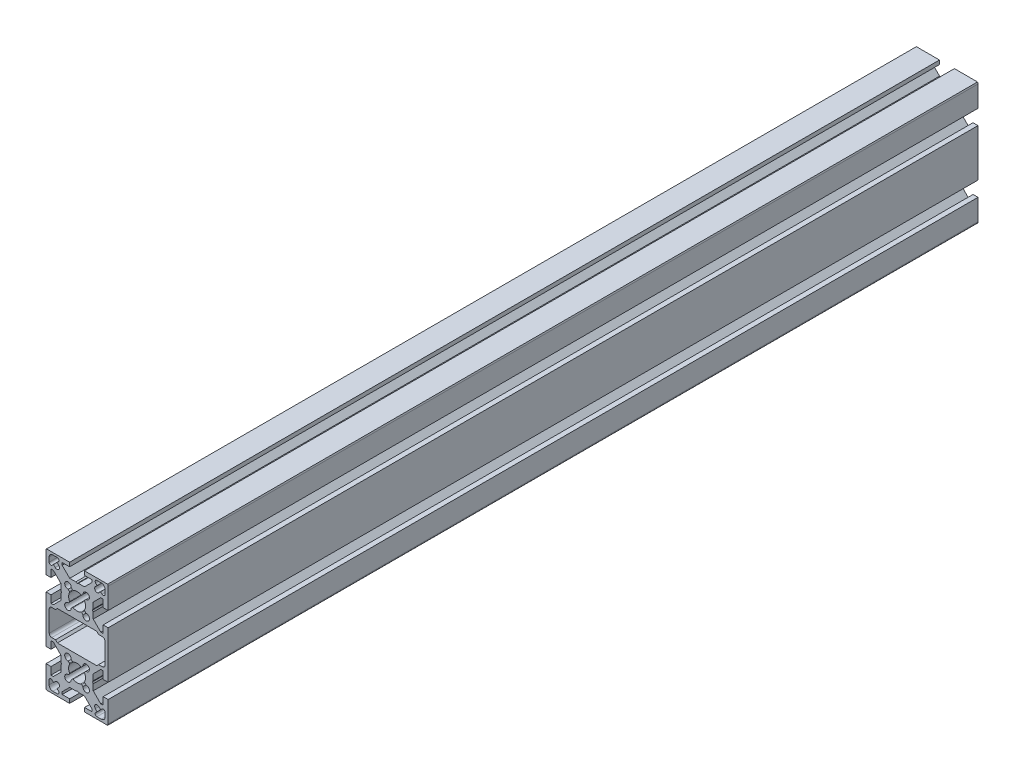
SolidWorks part; units mm, degrees
material "6061 Alloy"
ref_plane "Front Plane" through (0, 0, 0) normal (0, 0, 1) x (1, 0, 0)
ref_plane "Top Plane" through (0, 0, 0) normal (0, 1, 0) x (1, 0, 0)
ref_plane "Right Plane" through (0, 0, 0) normal (1, 0, 0) x (0, 0, -1)
ref_plane "Plane1" through (0, 0, -350) normal (0, 0, -1) x (-1, 0, 0)
sketch "Sketch1" plane through (0, 0, -350) normal (0, 0, -1) x (-1, 0, 0)
  line L0 (12.5, -15.5) -> (10.5, -15.5)
  line L1 (10.5, -15.5) -> (10.5, -18.5)
  line L2 (10.5, -18.5) -> (9.5355, -18.5)
  line L3 (9.5355, -18.5) -> (6.5, -15.4645)
  line L4 (6.5, -15.4645) -> (6.5, -13.0196)
  line L5 (6.5, -13.0196) -> (6.2, -12.5)
  line L6 (6.2, -12.5) -> (6.5, -11.9804)
  line L7 (6.5, -11.9804) -> (6.5, -9.5355)
  line L8 (6.5, -9.5355) -> (9.5355, -6.5)
  line L9 (9.5355, -6.5) -> (10.5, -6.5)
  line L10 (10.5, -6.5) -> (10.5, -9.5)
  line L11 (10.5, -9.5) -> (12.5, -9.5)
  line L12 (12.5, -9.5) -> (12.5, 9.5)
  line L13 (12.5, 9.5) -> (10.5, 9.5)
  line L14 (10.5, 9.5) -> (10.5, 6.5)
  line L15 (10.5, 6.5) -> (9.5355, 6.5)
  line L16 (9.5355, 6.5) -> (6.5, 9.5355)
  line L17 (6.5, 9.5355) -> (6.5, 11.9804)
  line L18 (6.5, 11.9804) -> (6.2, 12.5)
  line L19 (6.2, 12.5) -> (6.5, 13.0196)
  line L20 (6.5, 13.0196) -> (6.5, 15.4645)
  line L21 (6.5, 15.4645) -> (9.5355, 18.5)
  line L22 (9.5355, 18.5) -> (10.5, 18.5)
  line L23 (10.5, 18.5) -> (10.5, 15.5)
  line L24 (10.5, 15.5) -> (12.5, 15.5)
  line L25 (12.5, 15.5) -> (12.5, 24)
  line L26 (12.3, 24.6) -> (3, 24.6)
  line L27 (3, 24.6) -> (3, 23)
  line L28 (3, 23) -> (6, 23)
  line L29 (6, 23) -> (6, 22.0355)
  line L30 (6, 22.0355) -> (2.9645, 19)
  line L31 (2.9645, 19) -> (0.5196, 19)
  line L32 (0.5196, 19) -> (0, 18.7)
  line L33 (0, 18.7) -> (-0.5196, 19)
  line L34 (-0.5196, 19) -> (-2.9645, 19)
  line L35 (-2.9645, 19) -> (-6, 22.0355)
  line L36 (-6, 22.0355) -> (-6, 23)
  line L37 (-6, 23) -> (-3, 23)
  line L38 (-3, 23) -> (-3, 24.6)
  line L39 (-3, 24.6) -> (-12.3, 24.6)
  line L40 (-12.5, 24) -> (-12.5, 15.5)
  line L41 (-12.5, 15.5) -> (-10.5, 15.5)
  line L42 (-10.5, 15.5) -> (-10.5, 18.5)
  line L43 (-10.5, 18.5) -> (-9.5355, 18.5)
  line L44 (-9.5355, 18.5) -> (-6.5, 15.4645)
  line L45 (-6.5, 15.4645) -> (-6.5, 13.0196)
  line L46 (-6.5, 13.0196) -> (-6.2, 12.5)
  line L47 (-6.2, 12.5) -> (-6.5, 11.9804)
  line L48 (-6.5, 11.9804) -> (-6.5, 9.5355)
  line L49 (-6.5, 9.5355) -> (-9.5355, 6.5)
  line L50 (-9.5355, 6.5) -> (-10.5, 6.5)
  line L51 (-10.5, 6.5) -> (-10.5, 9.5)
  line L52 (-10.5, 9.5) -> (-12.5, 9.5)
  line L53 (-12.5, 9.5) -> (-12.5, -9.5)
  line L54 (-12.5, -9.5) -> (-10.5, -9.5)
  line L55 (-10.5, -9.5) -> (-10.5, -6.5)
  line L56 (-10.5, -6.5) -> (-9.5355, -6.5)
  line L57 (-9.5355, -6.5) -> (-6.5, -9.5355)
  line L58 (-6.5, -9.5355) -> (-6.5, -11.9804)
  line L59 (-6.5, -11.9804) -> (-6.2, -12.5)
  line L60 (-6.2, -12.5) -> (-6.5, -13.0196)
  line L61 (-6.5, -13.0196) -> (-6.5, -15.4645)
  line L62 (-6.5, -15.4645) -> (-9.5355, -18.5)
  line L63 (-9.5355, -18.5) -> (-10.5, -18.5)
  line L64 (-10.5, -18.5) -> (-10.5, -15.5)
  line L65 (-10.5, -15.5) -> (-12.5, -15.5)
  line L66 (-12.5, -15.5) -> (-12.5, -24)
  line L67 (-12.3, -24.6) -> (-3, -24.6)
  line L68 (-3, -24.6) -> (-3, -23)
  line L69 (-3, -23) -> (-6, -23)
  line L70 (-6, -23) -> (-6, -22.0355)
  line L71 (-6, -22.0355) -> (-2.9645, -19)
  line L72 (-2.9645, -19) -> (-0.5196, -19)
  line L73 (-0.5196, -19) -> (0, -18.7)
  line L74 (0, -18.7) -> (0.5196, -19)
  line L75 (0.5196, -19) -> (2.9645, -19)
  line L76 (2.9645, -19) -> (6, -22.0355)
  line L77 (6, -22.0355) -> (6, -23)
  line L78 (6, -23) -> (3, -23)
  line L79 (3, -23) -> (3, -24.6)
  line L80 (3, -24.6) -> (12.3, -24.6)
  line L81 (12.5, -24) -> (12.5, -15.5)
  line L82 (11.2, 4.25) -> (11.2, -4.25)
  line L83 (10.2, -5.25) -> (8.6642, -5.25)
  line L84 (8.6642, -5.25) -> (7.9142, -6)
  line L85 (7.9142, -6) -> (-7.9142, -6)
  line L86 (-7.9142, -6) -> (-8.6642, -5.25)
  line L87 (-8.6642, -5.25) -> (-10.2, -5.25)
  line L88 (-11.2, -4.25) -> (-11.2, 4.25)
  line L89 (-10.2, 5.25) -> (-8.6642, 5.25)
  line L90 (-8.6642, 5.25) -> (-7.9142, 6)
  line L91 (-7.9142, 6) -> (7.9142, 6)
  line L92 (7.9142, 6) -> (8.6642, 5.25)
  line L93 (8.6642, 5.25) -> (10.2, 5.25)
  line L94 (3.0878, -14.3857) -> (3.5825, -14.8804)
  line L95 (2.3804, -16.0825) -> (1.8857, -15.5878)
  line L96 (-1.8857, -15.5878) -> (-2.3804, -16.0825)
  line L97 (-3.5825, -14.8804) -> (-3.0878, -14.3857)
  line L98 (-3.0878, -10.6143) -> (-3.5825, -10.1196)
  line L99 (-2.3804, -8.9175) -> (-1.8857, -9.4122)
  line L100 (1.8857, -9.4122) -> (2.3804, -8.9175)
  line L101 (3.5825, -10.1196) -> (3.0878, -10.6143)
  line L102 (3.0878, 10.6143) -> (3.5825, 10.1196)
  line L103 (2.3804, 8.9175) -> (1.8857, 9.4122)
  line L104 (-1.8857, 9.4122) -> (-2.3804, 8.9175)
  line L105 (-3.5825, 10.1196) -> (-3.0878, 10.6143)
  line L106 (-3.0878, 14.3857) -> (-3.5825, 14.8804)
  line L107 (-2.3804, 16.0825) -> (-1.8857, 15.5878)
  line L108 (1.8857, 15.5878) -> (2.3804, 16.0825)
  line L109 (3.5825, 14.8804) -> (3.0878, 14.3857)
  line L110 (11.25, -20.4762) -> (11.25, -22.25)
  line L111 (9.75, -23.75) -> (7.9762, -23.75)
  line L112 (7.4812, -22.555) -> (8.061, -21.9752)
  line L113 (8.061, -21.9752) -> (7.3539, -21.2681)
  line L114 (8.7681, -19.8539) -> (9.4752, -20.561)
  line L115 (9.4752, -20.561) -> (10.055, -19.9812)
  line L116 (-9.4752, -20.561) -> (-8.7681, -19.8539)
  line L117 (-7.3539, -21.2681) -> (-8.061, -21.9752)
  line L118 (-8.061, -21.9752) -> (-7.4812, -22.555)
  line L119 (-7.9762, -23.75) -> (-9.75, -23.75)
  line L120 (-11.25, -22.25) -> (-11.25, -20.4762)
  line L121 (-10.055, -19.9812) -> (-9.4752, -20.561)
  line L122 (-8.061, 21.9752) -> (-7.3539, 21.2681)
  line L123 (-8.7681, 19.8539) -> (-9.4752, 20.561)
  line L124 (-9.4752, 20.561) -> (-10.055, 19.9812)
  line L125 (-11.25, 20.4762) -> (-11.25, 22.25)
  line L126 (-9.75, 23.75) -> (-7.9762, 23.75)
  line L127 (-7.4812, 22.555) -> (-8.061, 21.9752)
  line L128 (11.25, 22.25) -> (11.25, 20.4762)
  line L129 (10.055, 19.9812) -> (9.4752, 20.561)
  line L130 (9.4752, 20.561) -> (8.7681, 19.8539)
  line L131 (7.3539, 21.2681) -> (8.061, 21.9752)
  line L132 (8.061, 21.9752) -> (7.4812, 22.555)
  line L133 (7.9762, 23.75) -> (9.75, 23.75)
  arc A0 (12.5, 24) -> (12.3, 24.6) centre (11.5, 24) ccw
  arc A1 (-12.3, 24.6) -> (-12.5, 24) centre (-11.5, 24) ccw
  arc A2 (-12.5, -24) -> (-12.3, -24.6) centre (-11.5, -24) ccw
  arc A3 (12.3, -24.6) -> (12.5, -24) centre (11.5, -24) ccw
  arc A4 (10.2, 5.25) -> (11.2, 4.25) centre (10.2, 4.25) cw
  arc A5 (11.2, -4.25) -> (10.2, -5.25) centre (10.2, -4.25) cw
  arc A6 (-10.2, -5.25) -> (-11.2, -4.25) centre (-10.2, -4.25) cw
  arc A7 (-11.2, 4.25) -> (-10.2, 5.25) centre (-10.2, 4.25) cw
  arc A8 (3.0323, -14.0378) -> (3.0878, -14.3857) centre (3.2999, -14.1735) ccw
  arc A9 (3.5825, -14.8804) -> (2.3804, -16.0825) centre (3.677, -16.177) cw
  arc A10 (1.8857, -15.5878) -> (1.5378, -15.5323) centre (1.6735, -15.7999) ccw
  arc A11 (1.5378, -15.5323) -> (-1.5378, -15.5323) centre (0, -12.5) cw
  arc A12 (-1.5378, -15.5323) -> (-1.8857, -15.5878) centre (-1.6735, -15.7999) ccw
  arc A13 (-2.3804, -16.0825) -> (-3.5825, -14.8804) centre (-3.677, -16.177) cw
  arc A14 (-3.0878, -14.3857) -> (-3.0323, -14.0378) centre (-3.2999, -14.1735) ccw
  arc A15 (-3.0323, -14.0378) -> (-3.0323, -10.9622) centre (0, -12.5) cw
  arc A16 (-3.0323, -10.9622) -> (-3.0878, -10.6143) centre (-3.2999, -10.8265) ccw
  arc A17 (-3.5825, -10.1196) -> (-2.3804, -8.9175) centre (-3.677, -8.823) cw
  arc A18 (-1.8857, -9.4122) -> (-1.5378, -9.4677) centre (-1.6735, -9.2001) ccw
  arc A19 (-1.5378, -9.4677) -> (1.5378, -9.4677) centre (0, -12.5) cw
  arc A20 (1.5378, -9.4677) -> (1.8857, -9.4122) centre (1.6735, -9.2001) ccw
  arc A21 (2.3804, -8.9175) -> (3.5825, -10.1196) centre (3.677, -8.823) cw
  arc A22 (3.0878, -10.6143) -> (3.0323, -10.9622) centre (3.2999, -10.8265) ccw
  arc A23 (3.0323, -10.9622) -> (3.0323, -14.0378) centre (0, -12.5) cw
  arc A24 (3.0323, 10.9622) -> (3.0878, 10.6143) centre (3.2999, 10.8265) ccw
  arc A25 (3.5825, 10.1196) -> (2.3804, 8.9175) centre (3.677, 8.823) cw
  arc A26 (1.8857, 9.4122) -> (1.5378, 9.4677) centre (1.6735, 9.2001) ccw
  arc A27 (1.5378, 9.4677) -> (-1.5378, 9.4677) centre (0, 12.5) cw
  arc A28 (-1.5378, 9.4677) -> (-1.8857, 9.4122) centre (-1.6735, 9.2001) ccw
  arc A29 (-2.3804, 8.9175) -> (-3.5825, 10.1196) centre (-3.677, 8.823) cw
  arc A30 (-3.0878, 10.6143) -> (-3.0323, 10.9622) centre (-3.2999, 10.8265) ccw
  arc A31 (-3.0323, 10.9622) -> (-3.0323, 14.0378) centre (0, 12.5) cw
  arc A32 (-3.0323, 14.0378) -> (-3.0878, 14.3857) centre (-3.2999, 14.1735) ccw
  arc A33 (-3.5825, 14.8804) -> (-2.3804, 16.0825) centre (-3.677, 16.177) cw
  arc A34 (-1.8857, 15.5878) -> (-1.5378, 15.5323) centre (-1.6735, 15.7999) ccw
  arc A35 (-1.5378, 15.5323) -> (1.5378, 15.5323) centre (0, 12.5) cw
  arc A36 (1.5378, 15.5323) -> (1.8857, 15.5878) centre (1.6735, 15.7999) ccw
  arc A37 (2.3804, 16.0825) -> (3.5825, 14.8804) centre (3.677, 16.177) cw
  arc A38 (3.0878, 14.3857) -> (3.0323, 14.0378) centre (3.2999, 14.1735) ccw
  arc A39 (3.0323, 14.0378) -> (3.0323, 10.9622) centre (0, 12.5) cw
  arc A40 (10.055, -19.9812) -> (11.25, -20.4762) centre (10.55, -20.4762) cw
  arc A41 (11.25, -22.25) -> (9.75, -23.75) centre (9.75, -22.25) cw
  arc A42 (7.9762, -23.75) -> (7.4812, -22.555) centre (7.9762, -23.05) cw
  arc A43 (7.3539, -21.2681) -> (8.7681, -19.8539) centre (8.061, -20.561) cw
  arc A44 (-8.7681, -19.8539) -> (-7.3539, -21.2681) centre (-8.061, -20.561) cw
  arc A45 (-7.4812, -22.555) -> (-7.9762, -23.75) centre (-7.9762, -23.05) cw
  arc A46 (-9.75, -23.75) -> (-11.25, -22.25) centre (-9.75, -22.25) cw
  arc A47 (-11.25, -20.4762) -> (-10.055, -19.9812) centre (-10.55, -20.4762) cw
  arc A48 (-7.3539, 21.2681) -> (-8.7681, 19.8539) centre (-8.061, 20.561) cw
  arc A49 (-10.055, 19.9812) -> (-11.25, 20.4762) centre (-10.55, 20.4762) cw
  arc A50 (-11.25, 22.25) -> (-9.75, 23.75) centre (-9.75, 22.25) cw
  arc A51 (-7.9762, 23.75) -> (-7.4812, 22.555) centre (-7.9762, 23.05) cw
  arc A52 (11.25, 20.4762) -> (10.055, 19.9812) centre (10.55, 20.4762) cw
  arc A53 (8.7681, 19.8539) -> (7.3539, 21.2681) centre (8.061, 20.561) cw
  arc A54 (7.4812, 22.555) -> (7.9762, 23.75) centre (7.9762, 23.05) cw
  arc A55 (9.75, 23.75) -> (11.25, 22.25) centre (9.75, 22.25) cw
extrude "Boss-Extrude1" add sketch "Sketch1" against normal blind 350
